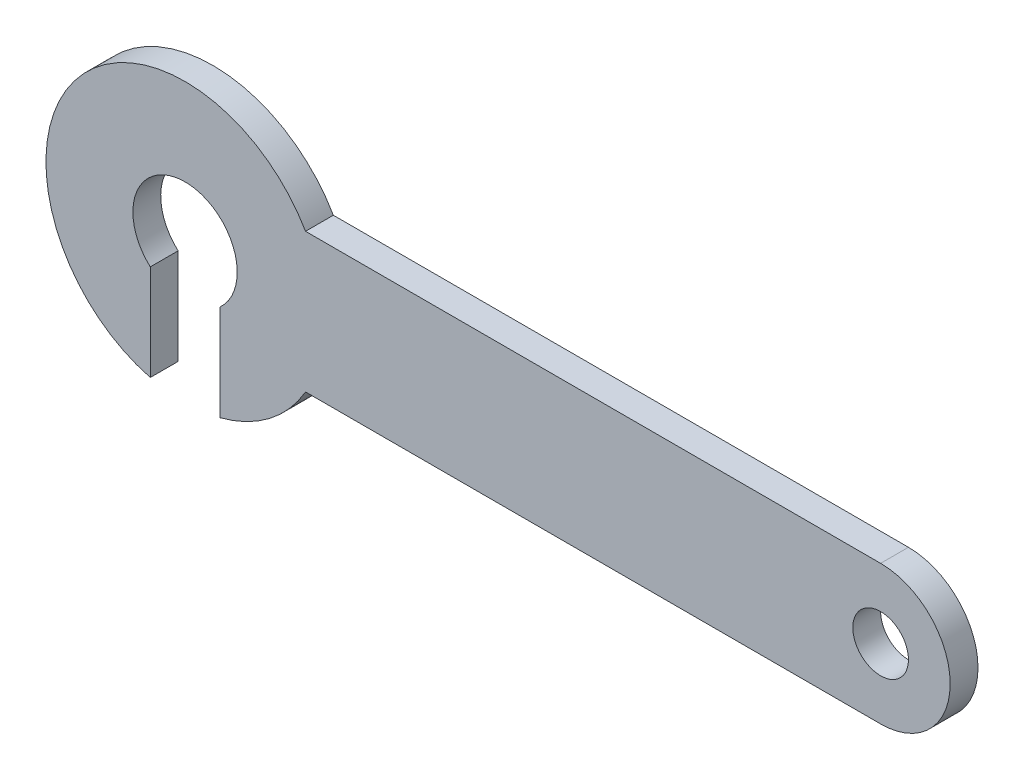
SolidWorks part; units mm, degrees
ref_plane "Front Plane" through (0, 0, 0) normal (0, 0, 1) x (1, 0, 0)
ref_plane "Top Plane" through (0, 0, 0) normal (0, 1, 0) x (1, 0, 0)
ref_plane "Right Plane" through (0, 0, 0) normal (1, 0, 0) x (0, 0, -1)
sketch "Sketch1" plane through (0, 0, 0) normal (0, 0, 1) x (1, 0, 0)
  line L0 (0, 0) -> (0, 10)
  line L1 (0, 10) -> (100, 10)
  line L2 (100, 10) -> (100, 0)
  line L3 (100, 0) -> (100, -10)
  line L4 (100, -10) -> (0, -10)
  line L5 (0, -10) -> (0, 0)
  circle A0 centre (0, 0) radius 20
  circle A1 centre (100, 0) radius 10
  dimension "D1" = 40
  dimension "D2" = 10
  dimension "D3" = 10
  dimension "D4" = 10
  dimension "D5" = 10
  dimension "D6" = 100
extrude "Boss-Extrude1" add sketch "Sketch1" along normal blind 4 contours L2 A1 L3 | L3 A1 L2 | A1 L1 A0 L4 | L4 A0 L1 L0 L5 | L1 A0 L4 L5 L0
sketch "Sketch2" plane through (0, 0, 0) normal (0, 0, 1) x (1, 0, 0)
  circle A0 centre (100, 0) radius 4
  dimension "D1" = 8
extrude "Cut-Extrude1" cut sketch "Sketch2" along normal blind 4
sketch "Sketch3" plane through (0, 0, 0) normal (0, 0, 1) x (1, 0, 0)
  circle A0 centre (0, 0) radius 7.5
  dimension "D1" = 15
extrude "Cut-Extrude2" cut sketch "Sketch3" along normal blind 4
sketch "Sketch4" plane through (0, 0, 0) normal (0, 0, 1) x (1, 0, 0)
  line L1 (5, -24.9161) -> (-5, -24.9161)
  line L2 (5, -24.9161) -> (5, -3.3822)
  line L3 (5, -3.3822) -> (-5, -3.3822)
  line L4 (-5, -24.9161) -> (-5, -3.3822)
  line L5 (5, -24.9161) -> (-5, -3.3822) construction
  line L6 (5, -3.3822) -> (-5, -24.9161) construction
  point P0 (0, -14.1492)
  dimension "D1" = 10
  dimension "D2" = 0
extrude "Cut-Extrude3" cut sketch "Sketch4" along normal blind 4
